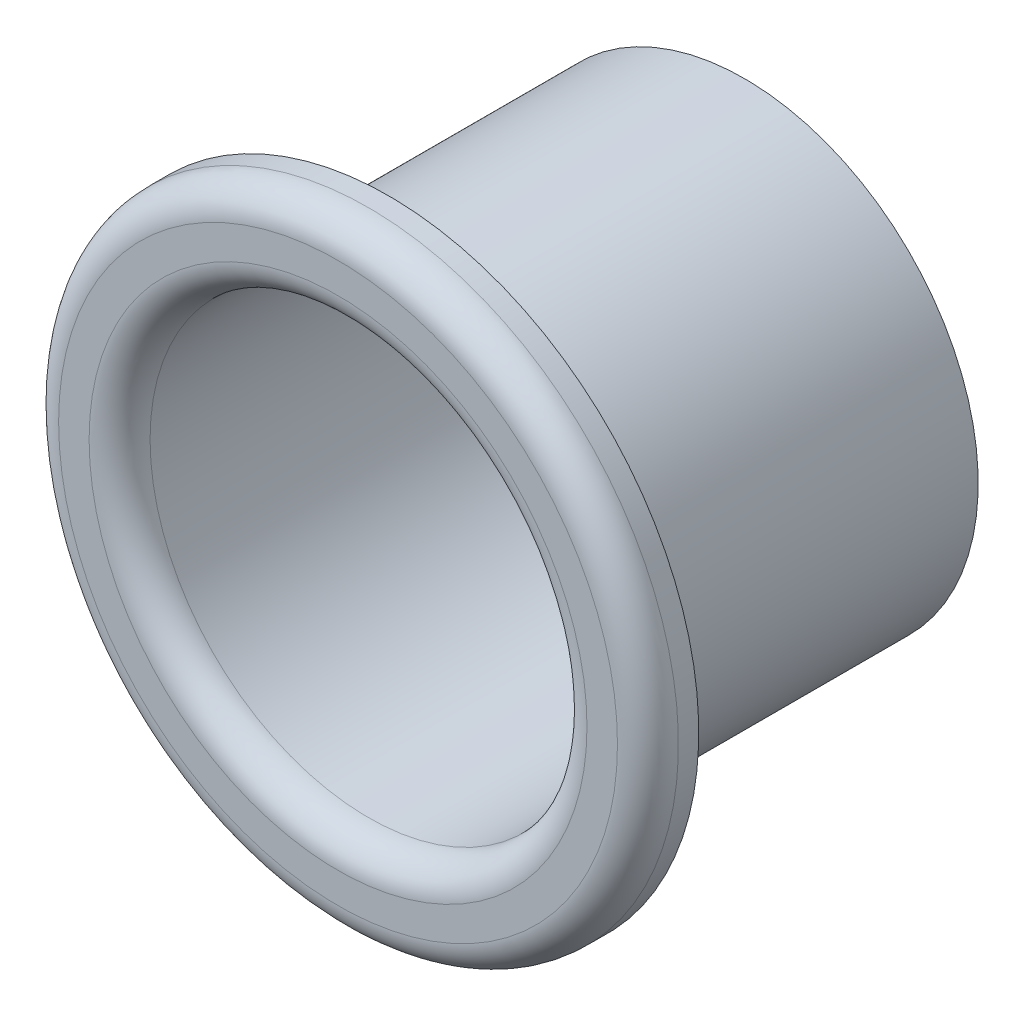
SolidWorks part; units mm, degrees
material "ASTM A36"
ref_plane "Plano frontal" through (0, 0, 0) normal (0, 0, 1) x (1, 0, 0)
ref_plane "Plano superior" through (0, 0, 0) normal (0, 1, 0) x (1, 0, 0)
ref_plane "Plano direito" through (0, 0, 0) normal (1, 0, 0) x (0, 0, -1)
sketch "Esboço1" plane through (0, 0, 0) normal (1, 0, 0) x (0, 0, -1)
  line L0 (0, 0) -> (-21758.4603, 0) construction
  line L1 (5, 30.5) -> (3, 30.5)
  line L2 (0, 27.5) -> (0, 24.5)
  line L3 (3, 21.5) -> (40, 21.5)
  line L4 (5, 29) -> (3, 29)
  line L5 (1.5, 27.5) -> (1.5, 24.5)
  line L6 (3, 23) -> (40, 23)
  line L7 (5, 29) -> (5, 30.5)
  line L8 (40, 23) -> (40, 21.5)
  arc A0 (3, 30.5) -> (0, 27.5) centre (3, 27.5) ccw
  arc A1 (0, 24.5) -> (3, 21.5) centre (3, 24.5) ccw
  arc A2 (3, 29) -> (1.5, 27.5) centre (3, 27.5) ccw
  arc A3 (1.5, 24.5) -> (3, 23) centre (3, 24.5) ccw
  dimension "D2" = 3
  dimension "D1" = 43
  dimension "D3" = 61
  dimension "D4" = 5
  dimension "D5" = 40
  dimension "D6" = 58
revolve "Revolução1" add sketch "Esboço1" angle 360 about L0
